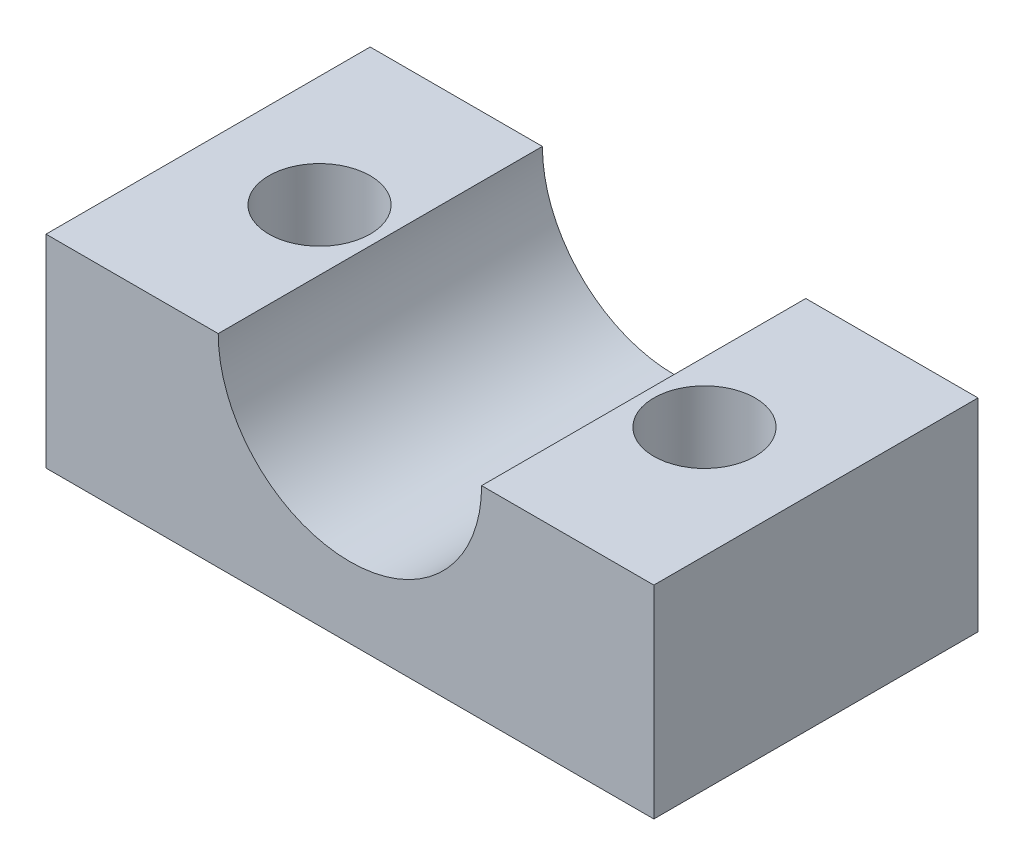
SolidWorks part; units mm, degrees
material "AISI 1015 Steel, Cold Drawn (SS)"
ref_plane "Front Plane" through (0, 0, 0) normal (0, 0, 1) x (1, 0, 0)
ref_plane "Top Plane" through (0, 0, 0) normal (0, 1, 0) x (1, 0, 0)
ref_plane "Right Plane" through (0, 0, 0) normal (1, 0, 0) x (0, 0, -1)
sketch "Sketch1" plane through (0, 0, 0) normal (0, 0, 1) x (1, 0, 0)
  line L0 (-30, 0) -> (-13, 0)
  line L1 (13, 0) -> (30, 0)
  line L2 (-30, 0) -> (-30, -20)
  line L3 (-30, -20) -> (30, -20)
  line L4 (30, -20) -> (30, 0)
  arc A0 (-13, 0) -> (13, 0) centre (0, 0) ccw
  point P1 (0, 0)
  point P6 (0, 0)
  dimension "D1" = 13
  dimension "D2" = 60
  dimension "D3" = 20
  dimension "D4" = 26
extrude "Boss-Extrude1" add sketch "Sketch1" along normal blind 32
sketch "Sketch2" plane through (0, -20, 0) normal (0, -1, 0) x (1, 0, 0)
  line L1 (-30, 32) -> (-30, 0) construction
  line L2 (-30, 0) -> (30, 0) construction
  line L3 (30, 32) -> (30, 0) construction
  circle A0 centre (-19, 16) radius 5
  circle A1 centre (19, 16) radius 5
  point P0 (0, 0)
  dimension "D1" = 10
  dimension "D2" = 11
  dimension "D3" = 11
  dimension "D4" = 16
extrude "Cut-Extrude1" cut sketch "Sketch2" against normal blind 32
